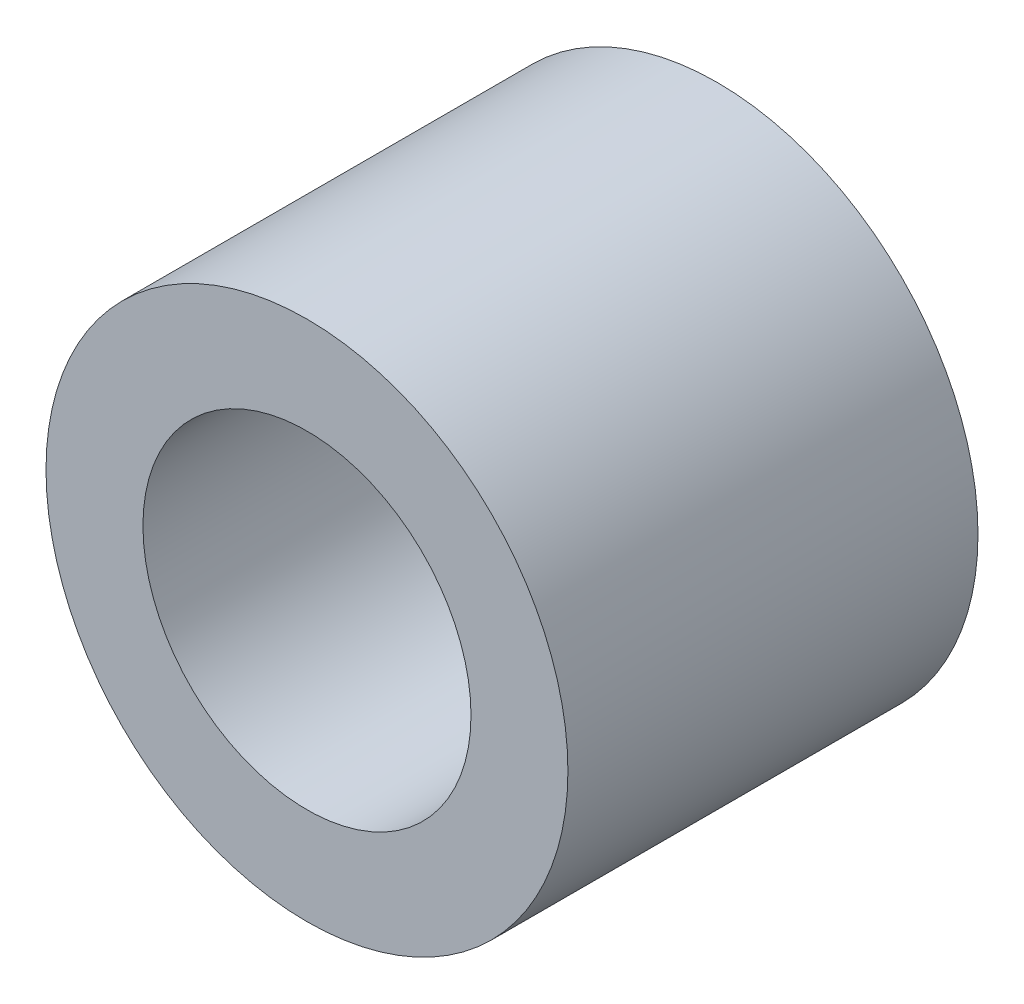
SolidWorks part; units mm, degrees
ref_plane "Front Plane" through (0, 0, 0) normal (0, 0, 1) x (1, 0, 0)
ref_plane "Top Plane" through (0, 0, 0) normal (0, 1, 0) x (1, 0, 0)
ref_plane "Right Plane" through (0, 0, 0) normal (1, 0, 0) x (0, 0, -1)
sketch "Sketch1" plane through (0, 0, 0) normal (0, 0, 1) x (1, 0, 0)
  circle A0 centre (0, 0) radius 4.4
  circle A1 centre (0, 0) radius 7
extrude "Boss-Extrude1" add sketch "Sketch1" along normal blind 11
